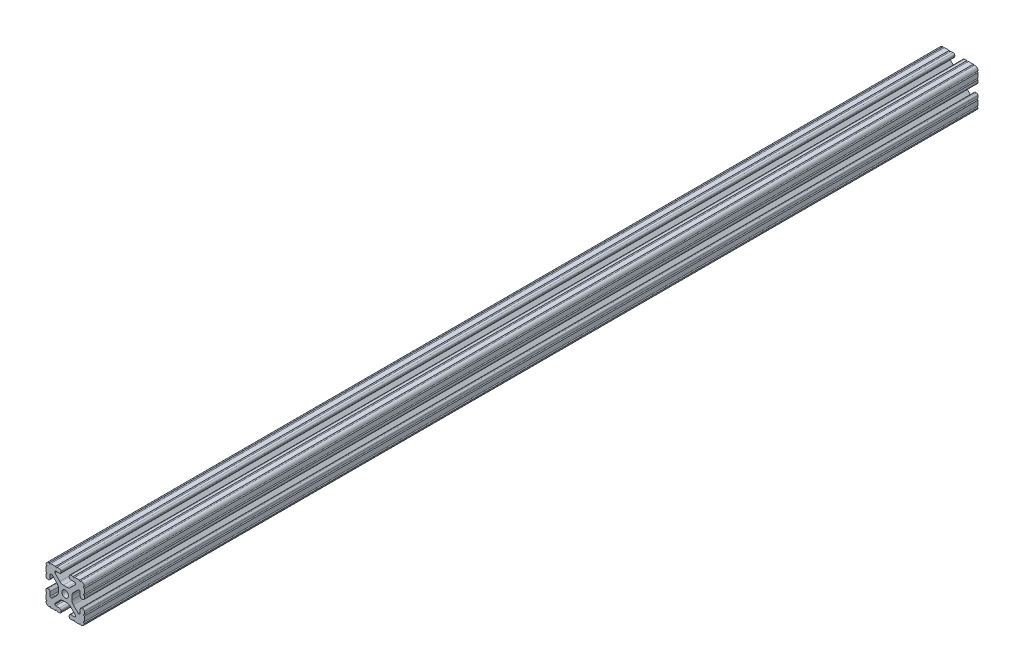
SolidWorks part; units mm, degrees
material "6105-T5 Aluminum"
ref_plane "Front Plane" through (0, 0, 0) normal (0, 0, 1) x (1, 0, 0)
ref_plane "Top Plane" through (0, 0, 0) normal (0, 1, 0) x (1, 0, 0)
ref_plane "Right Plane" through (0, 0, 0) normal (1, 0, 0) x (0, 0, -1)
sketch "Sketch1" plane through (0, 0, 0) normal (0, 0, 1) x (1, 0, 0)
  line L0 (-14.097, 10.287) -> (-13.5289, 10.287)
  line L1 (-12.9003, 10.0266) -> (-8.1292, 5.2555)
  line L2 (-6.738, 1.8969) -> (-6.738, -1.8969)
  line L3 (-8.1292, -5.2555) -> (-12.9003, -10.0266)
  line L4 (-13.5289, -10.287) -> (-14.097, -10.287)
  line L5 (-14.986, -9.398) -> (-14.986, -5.6388)
  line L6 (-16.5608, -4.064) -> (-17.4752, -4.064)
  line L7 (-19.05, -5.6388) -> (-19.05, -7.9756)
  line L8 (-19.05, -9.4996) -> (-19.05, -14.3256)
  line L9 (-19.05, -15.8496) -> (-19.05, -15.875)
  line L10 (-15.875, -19.05) -> (-15.8496, -19.05)
  line L11 (-14.3256, -19.05) -> (-9.4996, -19.05)
  line L12 (-7.9756, -19.05) -> (-5.6388, -19.05)
  line L13 (-4.064, -17.4752) -> (-4.064, -16.5608)
  line L14 (-5.6388, -14.986) -> (-9.398, -14.986)
  line L15 (-10.287, -14.097) -> (-10.287, -13.5289)
  line L16 (-10.0266, -12.9003) -> (-5.2555, -8.1292)
  line L17 (-1.8969, -6.738) -> (1.8969, -6.738)
  line L18 (5.2555, -8.1292) -> (10.0266, -12.9003)
  line L19 (10.287, -13.5289) -> (10.287, -14.097)
  line L20 (9.398, -14.986) -> (5.6388, -14.986)
  line L21 (4.064, -16.5608) -> (4.064, -17.4752)
  line L22 (5.6388, -19.05) -> (7.9756, -19.05)
  line L23 (9.4996, -19.05) -> (14.3256, -19.05)
  line L24 (15.8496, -19.05) -> (15.875, -19.05)
  line L25 (19.05, -15.875) -> (19.05, -15.8496)
  line L26 (19.05, -14.3256) -> (19.05, -9.4996)
  line L27 (19.05, -7.9756) -> (19.05, -5.6388)
  line L28 (17.4752, -4.064) -> (16.5608, -4.064)
  line L29 (14.986, -5.6388) -> (14.986, -9.398)
  line L30 (14.097, -10.287) -> (13.5289, -10.287)
  line L31 (12.9003, -10.0266) -> (8.1292, -5.2555)
  line L32 (6.738, -1.8969) -> (6.738, 1.8969)
  line L33 (8.1292, 5.2555) -> (12.9003, 10.0266)
  line L34 (13.5289, 10.287) -> (14.097, 10.287)
  line L35 (14.986, 9.398) -> (14.986, 5.6388)
  line L36 (16.5608, 4.064) -> (17.4752, 4.064)
  line L37 (19.05, 5.6388) -> (19.05, 7.9756)
  line L38 (19.05, 9.4996) -> (19.05, 14.3256)
  line L39 (19.05, 15.8496) -> (19.05, 15.875)
  line L40 (15.875, 19.05) -> (15.8496, 19.05)
  line L41 (14.3256, 19.05) -> (9.4996, 19.05)
  line L42 (7.9756, 19.05) -> (5.6388, 19.05)
  line L43 (4.064, 17.4752) -> (4.064, 16.5608)
  line L44 (5.6388, 14.986) -> (9.398, 14.986)
  line L45 (10.287, 14.097) -> (10.287, 13.5289)
  line L46 (10.0266, 12.9003) -> (5.2555, 8.1292)
  line L47 (1.8969, 6.738) -> (-1.8969, 6.738)
  line L48 (-5.2555, 8.1292) -> (-10.0266, 12.9003)
  line L49 (-10.287, 13.5289) -> (-10.287, 14.097)
  line L50 (-9.398, 14.986) -> (-5.6388, 14.986)
  line L51 (-4.064, 16.5608) -> (-4.064, 17.4752)
  line L52 (-5.6388, 19.05) -> (-7.9756, 19.05)
  line L53 (-9.4996, 19.05) -> (-14.3256, 19.05)
  line L54 (-15.8496, 19.05) -> (-15.875, 19.05)
  line L55 (-19.05, 15.875) -> (-19.05, 15.8496)
  line L56 (-19.05, 14.3256) -> (-19.05, 9.4996)
  line L57 (-19.05, 7.9756) -> (-19.05, 5.6388)
  line L58 (-17.4752, 4.064) -> (-16.5608, 4.064)
  line L59 (-14.986, 5.6388) -> (-14.986, 9.398)
  circle A0 centre (0, 0) radius 3.3274
  arc A1 (-14.097, 10.287) -> (-14.986, 9.398) centre (-14.097, 9.398) ccw
  arc A2 (-12.9003, 10.0266) -> (-13.5289, 10.287) centre (-13.5289, 9.398) ccw
  arc A3 (-6.738, 1.8969) -> (-8.1292, 5.2555) centre (-11.4878, 1.8969) ccw
  arc A4 (-8.1292, -5.2555) -> (-6.738, -1.8969) centre (-11.4878, -1.8969) ccw
  arc A5 (-13.5289, -10.287) -> (-12.9003, -10.0266) centre (-13.5289, -9.398) ccw
  arc A6 (-14.986, -9.398) -> (-14.097, -10.287) centre (-14.097, -9.398) ccw
  arc A7 (-14.986, -5.6388) -> (-16.5608, -4.064) centre (-16.5608, -5.6388) ccw
  arc A8 (-17.4752, -4.064) -> (-19.05, -5.6388) centre (-17.4752, -5.6388) ccw
  arc A9 (-19.05, -9.4996) -> (-19.05, -7.9756) centre (-19.05, -8.7376) ccw
  arc A10 (-19.05, -15.8496) -> (-19.05, -14.3256) centre (-19.05, -15.0876) ccw
  arc A11 (-19.05, -15.875) -> (-15.875, -19.05) centre (-15.875, -15.875) ccw
  arc A12 (-14.3256, -19.05) -> (-15.8496, -19.05) centre (-15.0876, -19.05) ccw
  arc A13 (-7.9756, -19.05) -> (-9.4996, -19.05) centre (-8.7376, -19.05) ccw
  arc A14 (-5.6388, -19.05) -> (-4.064, -17.4752) centre (-5.6388, -17.4752) ccw
  arc A15 (-4.064, -16.5608) -> (-5.6388, -14.986) centre (-5.6388, -16.5608) ccw
  arc A16 (-10.287, -14.097) -> (-9.398, -14.986) centre (-9.398, -14.097) ccw
  arc A17 (-10.0266, -12.9003) -> (-10.287, -13.5289) centre (-9.398, -13.5289) ccw
  arc A18 (-1.8969, -6.738) -> (-5.2555, -8.1292) centre (-1.8969, -11.4878) ccw
  arc A19 (5.2555, -8.1292) -> (1.8969, -6.738) centre (1.8969, -11.4878) ccw
  arc A20 (10.287, -13.5289) -> (10.0266, -12.9003) centre (9.398, -13.5289) ccw
  arc A21 (9.398, -14.986) -> (10.287, -14.097) centre (9.398, -14.097) ccw
  arc A22 (5.6388, -14.986) -> (4.064, -16.5608) centre (5.6388, -16.5608) ccw
  arc A23 (4.064, -17.4752) -> (5.6388, -19.05) centre (5.6388, -17.4752) ccw
  arc A24 (9.4996, -19.05) -> (7.9756, -19.05) centre (8.7376, -19.05) ccw
  arc A25 (15.8496, -19.05) -> (14.3256, -19.05) centre (15.0876, -19.05) ccw
  arc A26 (15.875, -19.05) -> (19.05, -15.875) centre (15.875, -15.875) ccw
  arc A27 (19.05, -14.3256) -> (19.05, -15.8496) centre (19.05, -15.0876) ccw
  arc A28 (19.05, -7.9756) -> (19.05, -9.4996) centre (19.05, -8.7376) ccw
  arc A29 (19.05, -5.6388) -> (17.4752, -4.064) centre (17.4752, -5.6388) ccw
  arc A30 (16.5608, -4.064) -> (14.986, -5.6388) centre (16.5608, -5.6388) ccw
  arc A31 (14.097, -10.287) -> (14.986, -9.398) centre (14.097, -9.398) ccw
  arc A32 (12.9003, -10.0266) -> (13.5289, -10.287) centre (13.5289, -9.398) ccw
  arc A33 (6.738, -1.8969) -> (8.1292, -5.2555) centre (11.4878, -1.8969) ccw
  arc A34 (8.1292, 5.2555) -> (6.738, 1.8969) centre (11.4878, 1.8969) ccw
  arc A35 (13.5289, 10.287) -> (12.9003, 10.0266) centre (13.5289, 9.398) ccw
  arc A36 (14.986, 9.398) -> (14.097, 10.287) centre (14.097, 9.398) ccw
  arc A37 (14.986, 5.6388) -> (16.5608, 4.064) centre (16.5608, 5.6388) ccw
  arc A38 (17.4752, 4.064) -> (19.05, 5.6388) centre (17.4752, 5.6388) ccw
  arc A39 (19.05, 9.4996) -> (19.05, 7.9756) centre (19.05, 8.7376) ccw
  arc A40 (19.05, 15.8496) -> (19.05, 14.3256) centre (19.05, 15.0876) ccw
  arc A41 (19.05, 15.875) -> (15.875, 19.05) centre (15.875, 15.875) ccw
  arc A42 (14.3256, 19.05) -> (15.8496, 19.05) centre (15.0876, 19.05) ccw
  arc A43 (7.9756, 19.05) -> (9.4996, 19.05) centre (8.7376, 19.05) ccw
  arc A44 (5.6388, 19.05) -> (4.064, 17.4752) centre (5.6388, 17.4752) ccw
  arc A45 (4.064, 16.5608) -> (5.6388, 14.986) centre (5.6388, 16.5608) ccw
  arc A46 (10.287, 14.097) -> (9.398, 14.986) centre (9.398, 14.097) ccw
  arc A47 (10.0266, 12.9003) -> (10.287, 13.5289) centre (9.398, 13.5289) ccw
  arc A48 (1.8969, 6.738) -> (5.2555, 8.1292) centre (1.8969, 11.4878) ccw
  arc A49 (-5.2555, 8.1292) -> (-1.8969, 6.738) centre (-1.8969, 11.4878) ccw
  arc A50 (-10.287, 13.5289) -> (-10.0266, 12.9003) centre (-9.398, 13.5289) ccw
  arc A51 (-9.398, 14.986) -> (-10.287, 14.097) centre (-9.398, 14.097) ccw
  arc A52 (-5.6388, 14.986) -> (-4.064, 16.5608) centre (-5.6388, 16.5608) ccw
  arc A53 (-4.064, 17.4752) -> (-5.6388, 19.05) centre (-5.6388, 17.4752) ccw
  arc A54 (-9.4996, 19.05) -> (-7.9756, 19.05) centre (-8.7376, 19.05) ccw
  arc A55 (-15.8496, 19.05) -> (-14.3256, 19.05) centre (-15.0876, 19.05) ccw
  arc A56 (-15.875, 19.05) -> (-19.05, 15.875) centre (-15.875, 15.875) ccw
  arc A57 (-19.05, 14.3256) -> (-19.05, 15.8496) centre (-19.05, 15.0876) ccw
  arc A58 (-19.05, 7.9756) -> (-19.05, 9.4996) centre (-19.05, 8.7376) ccw
  arc A59 (-19.05, 5.6388) -> (-17.4752, 4.064) centre (-17.4752, 5.6388) ccw
  arc A60 (-16.5608, 4.064) -> (-14.986, 5.6388) centre (-16.5608, 5.6388) ccw
extrude "Boss-Extrude1" add sketch "Sketch1" along normal blind 889
